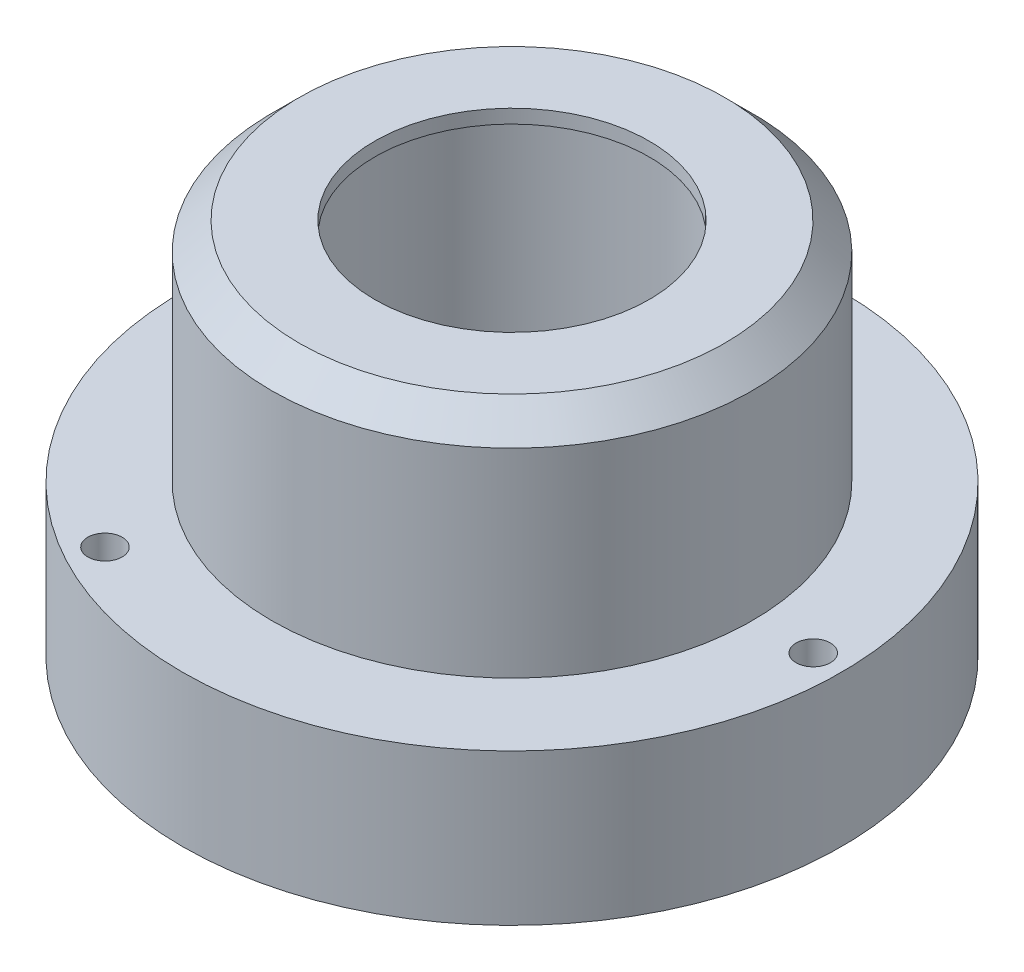
SolidWorks part; units mm, degrees
ref_plane "Plan de face" through (0, 0, 0) normal (0, 0, 1) x (1, 0, 0)
ref_plane "Plan de dessus" through (0, 0, 0) normal (0, 1, 0) x (1, 0, 0)
ref_plane "Plan de droite" through (0, 0, 0) normal (1, 0, 0) x (0, 0, -1)
sketch "Esquisse1" plane through (0, 0, 0) normal (0, 0, 1) x (1, 0, 0)
  line L0 (23.5, 0) -> (23.5, 53)
  line L1 (20, 55) -> (31, 55)
  line L2 (35, 51) -> (31, 55)
  line L4 (35, 51) -> (35, 22)
  line L5 (35, 22) -> (48, 22)
  line L6 (48, 22) -> (48, 0)
  line L7 (48, 0) -> (23.5, 0)
  line L8 (23.5, 53) -> (20, 53)
  line L9 (20, 53) -> (20, 55)
  line L10 (0, 45.2474) -> (0, -45.2474) construction
  dimension "D1" = 47
  dimension "D2" = 96
  dimension "D3" = 70
  dimension "D4" = 45
  dimension "D5" = 40
  dimension "D6" = 22
  dimension "D7" = 55
  dimension "D8" = 4
  dimension "D9" = 2
revolve "Révolution1" add sketch "Esquisse1" angle 360 about L10
hole_wizard "Trou taraudé M61" positions "Esquisse3D1" profile "Esquisse2" tap size "M6" standard "ISO"
sketch3d "Esquisse3D1"
  line L0 (0, 45.2474, 0) -> (0, -45.2474, 0) construction
  point P0 (43.4984, 22, -0.3779)
  dimension "D1" = 43.5
sketch "Esquisse2" plane through (43.4984, 22, -0.3779) normal (1, 0, 0) x (0, 0, 1)
  line L0 (0, 0) -> (0, 18.4434)
  line L1 (0, 18.4434) -> (2.5, 17)
  line L2 (2.5, 17) -> (2.5, 0)
  line L5 (2.5, 0) -> (0, 0)
  line L10 (0, 18.4434) -> (-2.5, 17) construction
  line L11 (0, -6.35) -> (0, 107.95) construction
  dimension "Diamètre du trou pour taraudage" = 5
  dimension "Profondeur du trou pour taraudage" = 17
  dimension "Angle de pointe" = 120
cosmetic thread "Filetage de perçage1" parameters "D1"=12, "D2"=6
hole_wizard "Trou taraudé M41" positions "Esquisse3D2" profile "Esquisse3" tap size "M4" standard "ISO"
sketch3d "Esquisse3D2"
  point P0 (28, 0, 0)
  dimension "D1" = 28
sketch "Esquisse3" plane through (28, 0, 0) normal (1, 0, 0) x (0, 0, -1)
  line L0 (0, 0) -> (0, 12.4526)
  line L1 (0, 12.4526) -> (1.65, 11.5)
  line L2 (1.65, 11.5) -> (1.65, 0)
  line L5 (1.65, 0) -> (0, 0)
  line L10 (0, 12.4526) -> (-1.65, 11.5) construction
  line L11 (0, -6.35) -> (0, 107.95) construction
  dimension "Diamètre du trou pour taraudage" = 3.3
  dimension "Profondeur du trou pour taraudage" = 11.5
  dimension "Angle de pointe" = 120
cosmetic thread "Filetage de perçage2" parameters "D1"=8, "D2"=4
hole_wizard "Trou taraudé M62" positions "Esquisse3D3" profile "Esquisse4" tap size "M6" standard "ISO"
sketch3d "Esquisse3D3"
  point P0 (-43, 0, 0)
  dimension "D1" = 43
sketch "Esquisse4" plane through (-43, 0, 0) normal (1, 0, 0) x (0, 0, -1)
  line L0 (0, 0) -> (0, 18.4434)
  line L1 (0, 18.4434) -> (2.5, 17)
  line L2 (2.5, 17) -> (2.5, 0)
  line L5 (2.5, 0) -> (0, 0)
  line L10 (0, 18.4434) -> (-2.5, 17) construction
  line L11 (0, -6.35) -> (0, 107.95) construction
  dimension "Diamètre du trou pour taraudage" = 5
  dimension "Profondeur du trou pour taraudage" = 17
  dimension "Angle de pointe" = 120
cosmetic thread "Filetage de perçage3" parameters "D1"=12, "D2"=6
pattern_circular "Répétition circulaire1" count 3 every 120 about axis through (0, 0, 0) along (0, 1, 0) of "Trou taraudé M61", "Trou taraudé M41", "Trou taraudé M62"
